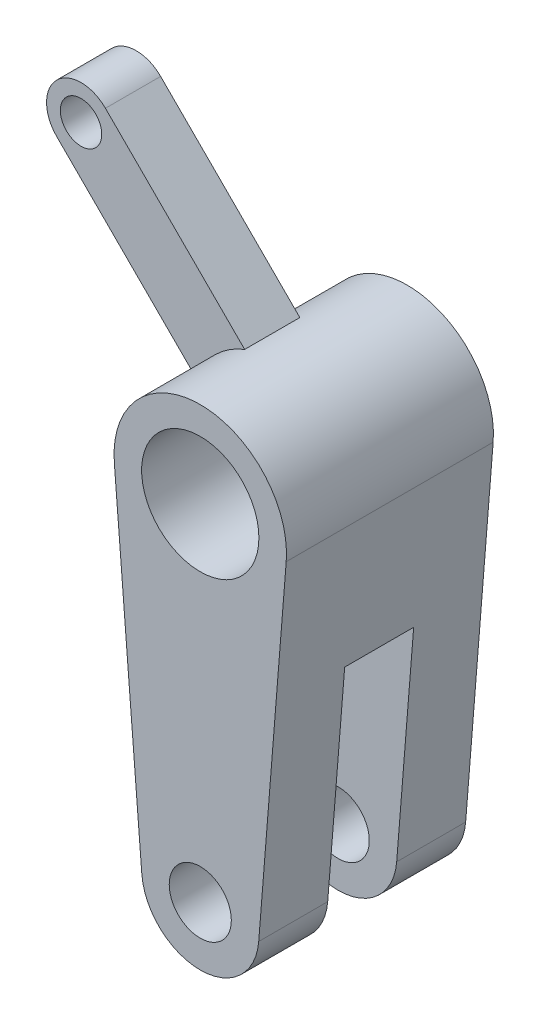
SolidWorks part; units mm, degrees
ref_plane "Спереди" through (0, 0, 0) normal (0, 0, 1) x (1, 0, 0)
ref_plane "Сверху" through (0, 0, 0) normal (0, 1, 0) x (1, 0, 0)
ref_plane "Справа" through (0, 0, 0) normal (1, 0, 0) x (0, 0, -1)
sketch "Эскиз1" plane through (0, 0, 0) normal (0, 0, 1) x (1, 0, 0)
  line L0 (0, 0) -> (0, -50) construction
  line L1 (-12.4599, -1) -> (-8.4728, -50.68)
  line L2 (12.4599, -1) -> (8.4728, -50.68)
  circle A0 centre (0, 0) radius 12.5
  circle A1 centre (0, -50) radius 8.5
  circle A2 centre (0, 0) radius 8.5
  circle A3 centre (0, -50) radius 4.5
  dimension "D1" = 25
  dimension "D2" = 17
  dimension "D3" = 50
  dimension "D4" = 4
  dimension "D5" = 4
extrude "Бобышка-Вытянуть1" add sketch "Эскиз1" along normal mid plane 30
sketch "Эскиз2" plane through (0, 0, 0) normal (0, 0, 1) x (1, 0, 0)
  line L1 (-15, -80) -> (15, -80)
  line L2 (-15, -80) -> (-15, -20)
  line L3 (-15, -20) -> (15, -20)
  line L4 (15, -80) -> (15, -20)
  line L5 (-15, -80) -> (15, -20) construction
  line L6 (-15, -20) -> (15, -80) construction
  point P0 (0, -50)
  dimension "D1" = 30
  dimension "D2" = 60
extrude "Вырез-Вытянуть1" cut sketch "Эскиз2" against normal mid plane 10
sketch "Эскиз3" plane through (0, 0, 0) normal (0, 0, 1) x (1, 0, 0)
  line L0 (0, 0) -> (-28.2843, 28.2843) construction
  line L1 (-3.5355, -3.5355) -> (-31.8198, 24.7487)
  line L2 (3.5355, 3.5355) -> (-24.7487, 31.8198)
  line L3 (0, 0) -> (0, 22.3545) construction
  arc A0 (-3.5355, -3.5355) -> (3.5355, 3.5355) centre (0, 0) ccw
  arc A1 (-24.7487, 31.8198) -> (-31.8198, 24.7487) centre (-28.2843, 28.2843) ccw
  circle A2 centre (-28.2843, 28.2843) radius 3
  arc A3 (12.4599, -1) -> (-12.4599, -1) centre (0, 0) ccw construction
  arc A4 (12.4599, -1) -> (-12.4599, -1) centre (0, 0) ccw
  point P3 (-14.1421, 14.1421)
  dimension "D4" = 6
  dimension "D1" = 10
  dimension "D2" = 40
  dimension "D3" = 45
extrude "Бобышка-Вытянуть2" add sketch "Эскиз3" along normal mid plane 8 contours A4 L2 A1 L1 A2
